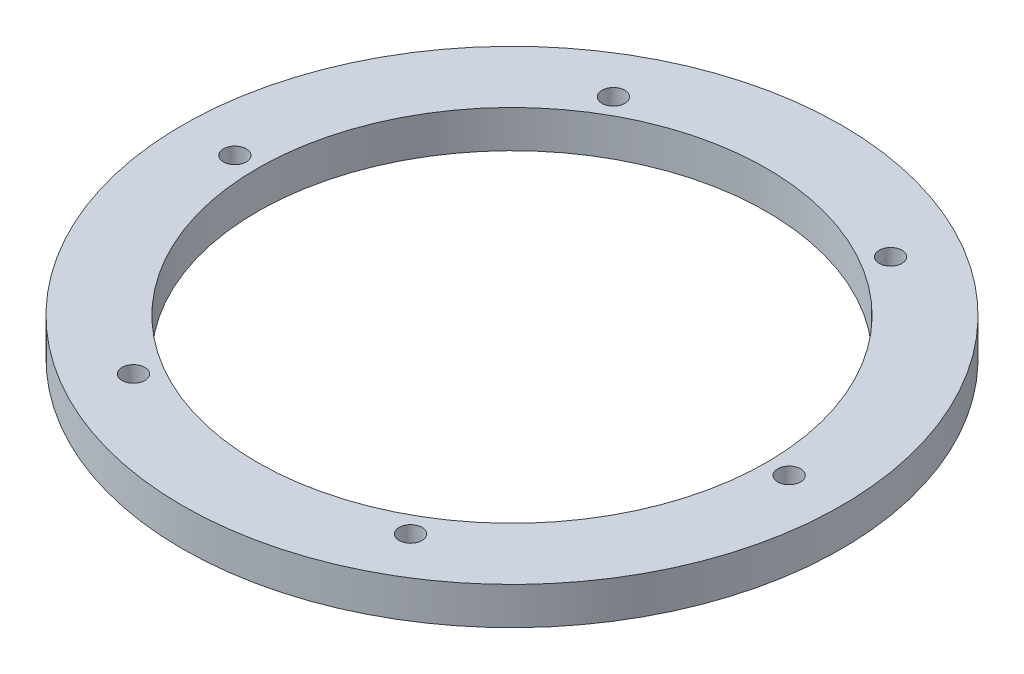
SolidWorks part; units mm, degrees
ref_plane "前视基准面" through (0, 0, 0) normal (0, 0, 1) x (1, 0, 0)
ref_plane "上视基准面" through (0, 0, 0) normal (0, 1, 0) x (1, 0, 0)
ref_plane "右视基准面" through (0, 0, 0) normal (1, 0, 0) x (0, 0, -1)
other "Configuration Table"
sketch "草图1" plane through (0, 0, 0) normal (0, 1, 0) x (1, 0, 0)
  line L0 (34, 0) -> (40, 0) construction
  line L1 (40, 0) -> (44, 0) construction
  circle A0 centre (0, 0) radius 34
  circle A1 centre (0, 0) radius 44
  circle A2 centre (0, 0) radius 40 construction
  circle A3 centre (37, 0) radius 1.525
  circle A4 centre (18.5, -32.0429) radius 1.525
  circle A5 centre (-18.5, -32.0429) radius 1.525
  circle A6 centre (-37, 0) radius 1.525
  circle A7 centre (-18.5, 32.0429) radius 1.525
  circle A8 centre (18.5, 32.0429) radius 1.525
  point P22 (0, 0)
  dimension "D1" = 80
  dimension "D4" = 3.05
  dimension "D2" = 6
  dimension "D3" = 4
  dimension "D5" = 6
extrude "凸台-拉伸1" add sketch "草图1" along normal blind 5
